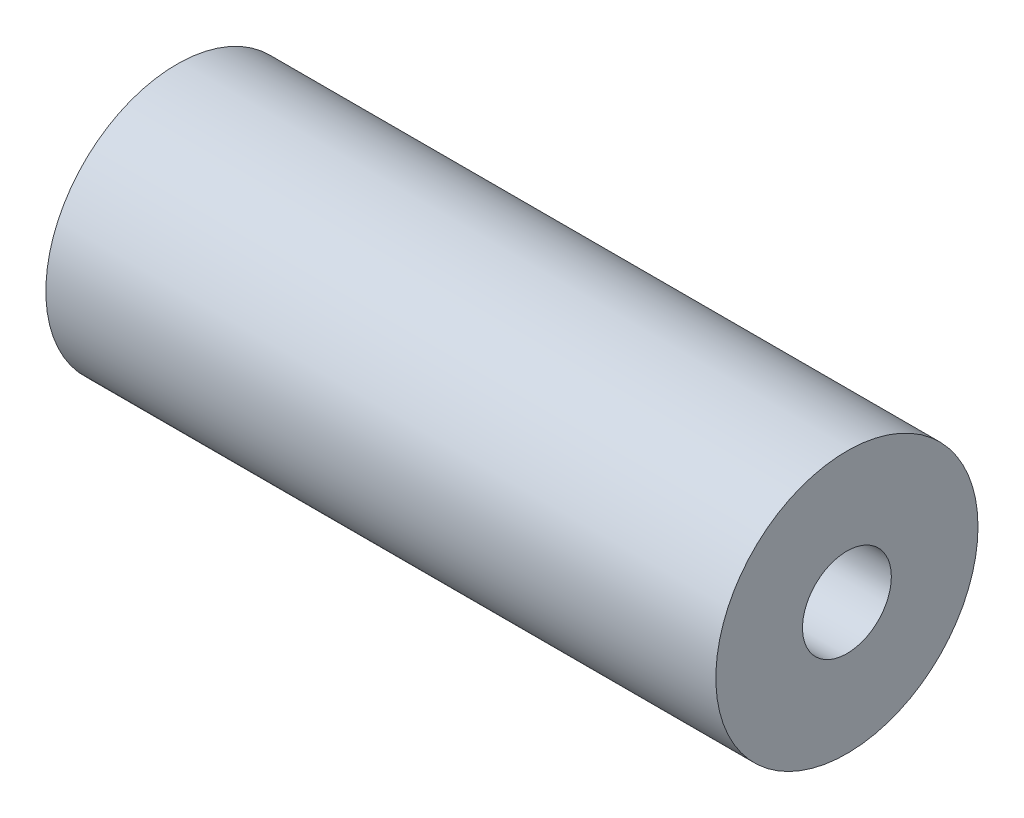
SolidWorks part; units mm, degrees
ref_plane "Front Plane" through (0, 0, 0) normal (1, 0, 0) x (0, 1, 0)
ref_plane "Top Plane" through (0, 0, 0) normal (0, 0, 1) x (0, 1, 0)
ref_plane "Right Plane" through (0, 0, 0) normal (0, 1, 0) x (-1, 0, 0)
sketch "Sketch1" plane through (0, 0, 0) normal (1, 0, 0) x (0, 1, 0)
  line L0 (-1.9975, 2.5) -> (1.9975, 2.5)
  circle A0 centre (0, 0) radius 3.2 construction
  circle A1 centre (0, 0) radius 4.5
  circle A2 centre (0, 0) radius 3
  dimension "D1" = 0.2
  dimension "D2" = 6
  dimension "D4" = 9
  dimension "D3" = 2.5
extrude "Boss-Extrude1" add sketch "Sketch1" along normal blind 14
sketch "Sketch2" plane through (14, 0, 0) normal (1, 0, 0) x (0, 1, 0)
  circle A0 centre (0, 0) radius 4.5
  dimension "D1" = 9
extrude "Boss-Extrude2" add sketch "Sketch2" along normal blind 2
sketch "Sketch3" plane through (16, 0, 0) normal (1, 0, 0) x (0, 1, 0)
  line L1 (-0.5, 2.025) -> (0.5, 2.025) construction
  line L2 (-0.5, 2.025) -> (-0.5, 1.025) construction
  line L3 (-0.5, 1.025) -> (0.5, 1.025) construction
  line L4 (0.5, 2.025) -> (0.5, 1.025) construction
  line L5 (-0.5, 2.025) -> (0.5, 1.025) construction
  line L6 (-0.5, 1.025) -> (0.5, 2.025) construction
  circle A0 centre (0, 0) radius 1.525
  point P3 (0, 1.525)
  circle M1 centre (0, 0) radius 4.5
  dimension "D1" = 3.05
  dimension "D2" = 1
  dimension "D3" = 1
extrude "Boss-Extrude3" add sketch "Sketch3" along normal blind 7 contours A0 M1
